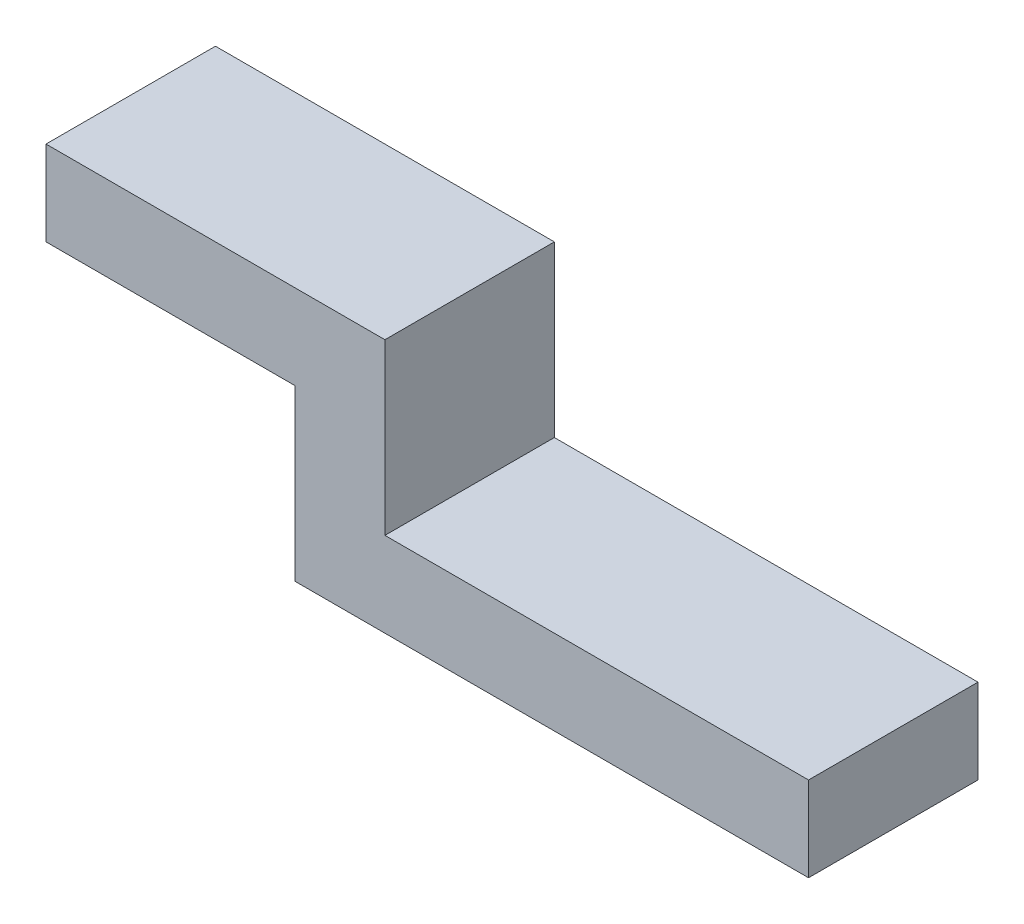
SolidWorks part; units mm, degrees
ref_plane "Front Plane" through (0, 0, 0) normal (0, 0, 1) x (1, 0, 0)
ref_plane "Top Plane" through (0, 0, 0) normal (0, 1, 0) x (1, 0, 0)
ref_plane "Right Plane" through (0, 0, 0) normal (1, 0, 0) x (0, 0, -1)
sketch "Sketch1" plane through (0, 0, 0) normal (0, 0, 1) x (1, 0, 0)
  line L33 (0, 19.5593) -> (7.6944, 19.5593)
  line L34 (0, 19.5593) -> (0, 22.0993)
  line L35 (0, 22.0993) -> (-3.7356, 22.0993)
  line L36 (-3.7356, 22.0993) -> (-3.7356, 23.3693)
  line L37 (-3.7356, 23.3693) -> (1.3444, 23.3693)
  line L38 (1.3444, 23.3693) -> (1.3444, 20.8293)
  line L39 (1.3444, 20.8293) -> (7.6944, 20.8293)
  line L40 (7.6944, 20.8293) -> (7.6944, 19.5593)
  dimension "D1" = 5.08
  dimension "D5" = 6.35
  dimension "D2" = 1.27
  dimension "D3" = 2.54
  dimension "D4" = 1.27
extrude "Boss-Extrude8" add sketch "Sketch1" along normal blind 2.54
